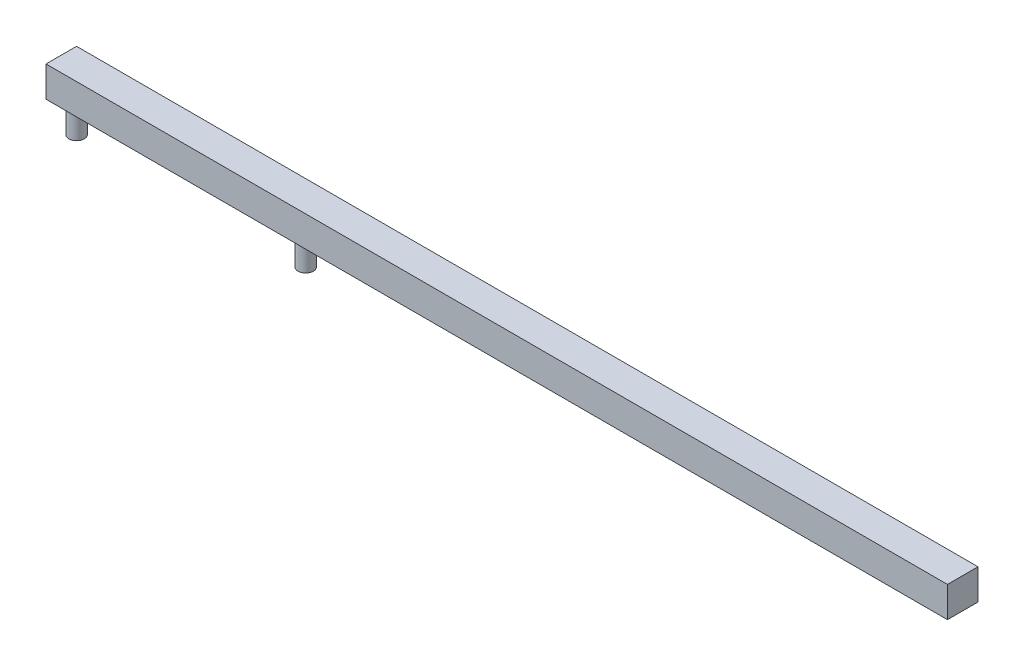
SolidWorks part; units mm, degrees
ref_plane "Plan de face" through (0, 0, 0) normal (0, 0, 1) x (1, 0, 0)
ref_plane "Plan de dessus" through (0, 0, 0) normal (0, 1, 0) x (1, 0, 0)
ref_plane "Plan de droite" through (0, 0, 0) normal (1, 0, 0) x (0, 0, -1)
sketch "Esquisse1" plane through (0, 0, 0) normal (0, 1, 0) x (1, 0, 0)
  line L1 (0, 0) -> (-295, 0)
  line L2 (0, 0) -> (0, -10)
  line L3 (0, -10) -> (-295, -10)
  line L4 (-295, 0) -> (-295, -10)
  dimension "D1" = 295
  dimension "D2" = 10
extrude "Boss.-Extru.1" add sketch "Esquisse1" along normal blind 10
sketch "Esquisse2" plane through (0, 0, 0) normal (0, -1, 0) x (-1, 0, 0)
  line L0 (295, -5) -> (0, -5) construction
  line L1 (295, 0) -> (295, -10) construction
  line L2 (0, -10) -> (0, 0) construction
  circle A0 centre (290, -5) radius 2.5
  circle A1 centre (215, -5) radius 2.5
  dimension "D1" = 5
  dimension "D4" = 5
  dimension "D2" = 5
  dimension "D3" = 75
extrude "Boss.-Extru.2" add sketch "Esquisse2" along normal blind 10
sketch "Esquisse5" plane through (0, 10, 0) normal (0, 1, 0) x (1, 0, 0)
  line L0 (-25, 0) -> (-25, -10) construction
  line L3 (0, 0) -> (-295, 0) construction
  line L4 (-295, -10) -> (0, -10) construction
  dimension "D1" = 25
